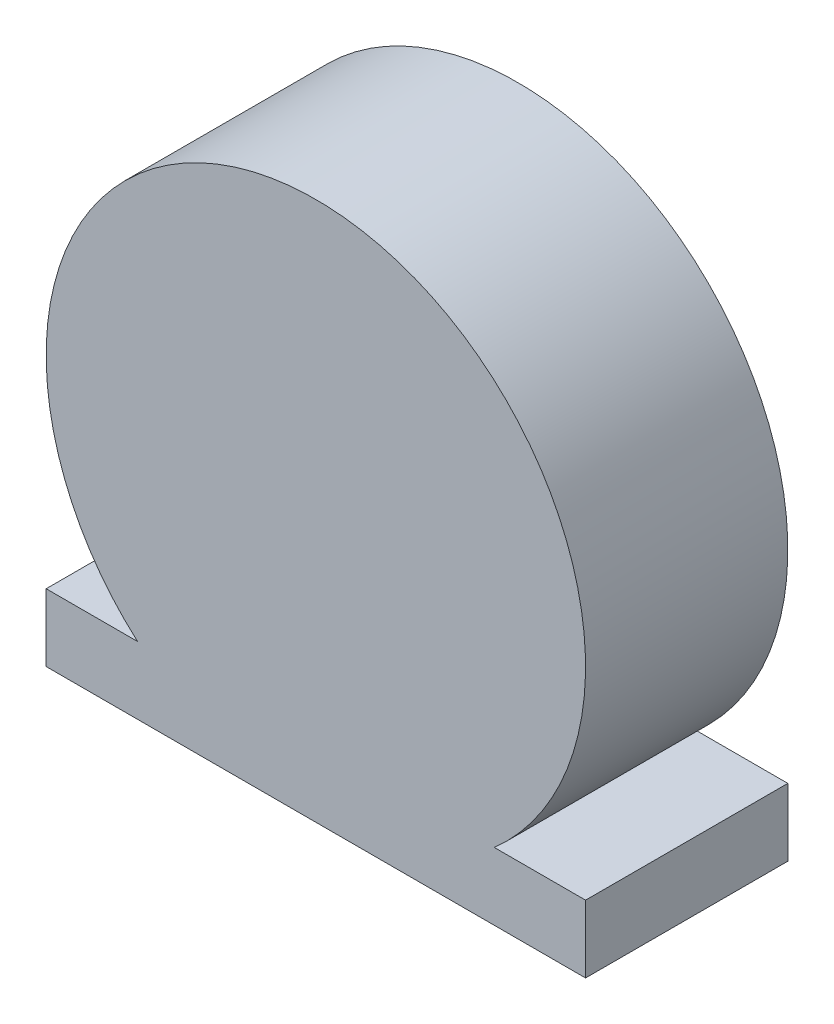
SolidWorks part; units mm, degrees
ref_plane "Front Plane" through (0, 0, 0) normal (0, 0, 1) x (1, 0, 0)
ref_plane "Top Plane" through (0, 0, 0) normal (0, 1, 0) x (1, 0, 0)
ref_plane "Right Plane" through (0, 0, 0) normal (1, 0, 0) x (0, 0, -1)
sketch "Sketch1" plane through (0, 0, 0) normal (0, 0, 1) x (1, 0, 0)
  circle A0 centre (0, 0) radius 20
  dimension "D1" = 40
extrude "Boss-Extrude1" add sketch "Sketch1" along normal blind 15
sketch "Sketch2" plane through (0, 0, 0) normal (0, 0, -1) x (-1, 0, 0)
  line L1 (20, -15) -> (-20, -15)
  line L2 (20, -15) -> (20, -20)
  line L3 (20, -20) -> (-20, -20)
  line L4 (-20, -15) -> (-20, -20)
  circle A0 centre (0, 0) radius 20 construction
  dimension "D2" = 20
  dimension "D1" = 5
  dimension "D3" = 40
  dimension "D4" = 20
extrude "Boss-Extrude2" add sketch "Sketch2" against normal blind 15
sketch "Sketch3" plane through (0, 0, 0) normal (0, 0, -1) x (-1, 0, 0)
  circle A0 centre (0, 0) radius 15.875
  dimension "D1" = 31.75
extrude "Cut-Extrude1" cut sketch "Sketch3" against normal blind 10
